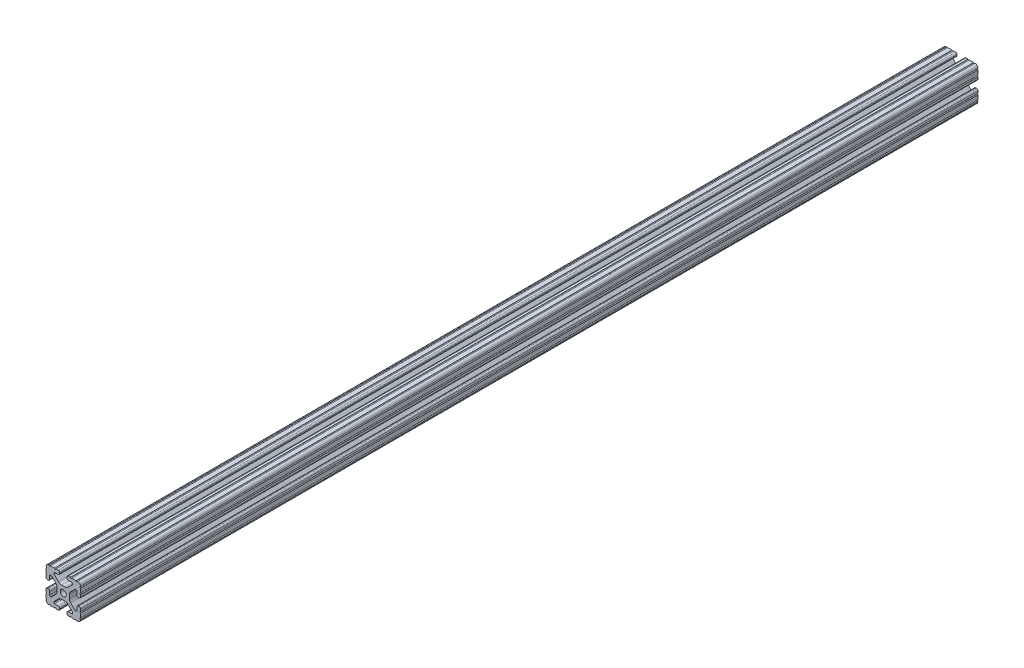
SolidWorks part; units mm, degrees
material "6061 Alloy"
ref_plane "Front Plane" through (0, 0, 0) normal (0, 0, 1) x (1, 0, 0)
ref_plane "Top Plane" through (0, 0, 0) normal (0, 1, 0) x (1, 0, 0)
ref_plane "Right Plane" through (0, 0, 0) normal (1, 0, 0) x (0, 0, -1)
sketch "Sketch1" plane through (0, 0, 0) normal (0, 0, 1) x (1, 0, 0)
  line L0 (0, 25.6181) -> (0, -24.623) construction
  line L1 (-20.8943, 0) -> (20.4607, 0) construction
  line L2 (-10.0229, 12.9148) -> (-5.2522, 8.144)
  line L3 (-10.287, 14.0843) -> (-10.287, 13.5524)
  line L4 (-5.6176, 14.986) -> (-9.3853, 14.986)
  line L5 (-4.064, 17.4964) -> (-4.064, 16.5396)
  line L6 (-7.9742, 19.05) -> (-5.6176, 19.05)
  line L7 (-14.3277, 19.05) -> (-9.4982, 19.05)
  line L8 (-19.05, 9.4961) -> (-19.05, 14.3277)
  line L9 (-19.05, 5.6176) -> (-19.05, 7.9763)
  line L10 (-16.5396, 4.064) -> (-17.4964, 4.064)
  line L11 (-14.986, 9.3853) -> (-14.986, 5.6176)
  line L12 (-13.516, 10.287) -> (-14.0843, 10.287)
  line L13 (-8.1476, 5.2921) -> (-12.8784, 10.0229)
  line L14 (-6.7564, -1.9335) -> (-6.7564, 1.9335)
  line L15 (-12.8784, -10.0229) -> (-8.1476, -5.2921)
  line L16 (-14.0843, -10.287) -> (-13.516, -10.287)
  line L17 (-14.986, -5.6176) -> (-14.986, -9.3853)
  line L18 (-17.4964, -4.064) -> (-16.5396, -4.064)
  line L19 (-19.05, -7.9763) -> (-19.05, -5.6176)
  line L20 (-19.05, -14.3277) -> (-19.05, -9.4961)
  line L21 (-9.4961, -19.05) -> (-14.3277, -19.05)
  line L22 (-5.6176, -19.05) -> (-7.9763, -19.05)
  line L23 (-4.064, -17.4964) -> (-4.064, -16.5396)
  line L24 (10.0229, -12.9148) -> (5.2522, -8.144)
  line L25 (10.287, -14.0843) -> (10.287, -13.5524)
  line L26 (5.6176, -14.986) -> (9.3853, -14.986)
  line L28 (-1.9022, 6.7564) -> (1.9022, 6.7564)
  line L29 (-1.9022, -6.7564) -> (1.9022, -6.7564)
  line L31 (-5.6176, -14.986) -> (-9.3853, -14.986)
  line L32 (-10.287, -14.0843) -> (-10.287, -13.5524)
  line L33 (-10.0229, -12.9148) -> (-5.2522, -8.144)
  line L66 (4.064, -16.5396) -> (4.064, -17.4964)
  line L67 (5.6176, -19.05) -> (7.9763, -19.05)
  line L68 (9.4961, -19.05) -> (14.3277, -19.05)
  line L69 (19.05, -14.3277) -> (19.05, -9.4961)
  line L70 (19.05, -7.9763) -> (19.05, -5.6176)
  line L71 (17.4964, -4.064) -> (16.5396, -4.064)
  line L72 (14.986, -5.6176) -> (14.986, -9.3853)
  line L73 (14.0843, -10.287) -> (13.516, -10.287)
  line L74 (12.8784, -10.0229) -> (8.1476, -5.2921)
  line L75 (6.7564, -1.9335) -> (6.7564, 1.9335)
  line L76 (8.1476, 5.2921) -> (12.8784, 10.0229)
  line L77 (13.516, 10.287) -> (14.0843, 10.287)
  line L78 (14.986, 9.3853) -> (14.986, 5.6176)
  line L79 (16.5396, 4.064) -> (17.4964, 4.064)
  line L80 (19.05, 5.6176) -> (19.05, 7.9763)
  line L81 (19.05, 9.4961) -> (19.05, 14.3277)
  line L82 (14.3277, 19.05) -> (9.4982, 19.05)
  line L83 (7.9742, 19.05) -> (5.6176, 19.05)
  line L84 (4.064, 17.4964) -> (4.064, 16.5396)
  line L85 (5.6176, 14.986) -> (9.3853, 14.986)
  line L86 (10.287, 14.0843) -> (10.287, 13.5524)
  line L87 (10.0229, 12.9148) -> (5.2522, 8.144)
  arc A0 (-10.0229, 12.9148) -> (-10.287, 13.5524) centre (-9.3853, 13.5524) cw
  circle A1 centre (0, 0) radius 3.3274
  arc A2 (-10.287, 14.0843) -> (-9.3853, 14.986) centre (-9.3853, 14.0843) cw
  arc A3 (-4.064, 16.5396) -> (-5.6176, 14.986) centre (-5.6176, 16.5396) cw
  arc A4 (-5.6176, 19.05) -> (-4.064, 17.4964) centre (-5.6176, 17.4964) cw
  arc A5 (-7.9742, 19.05) -> (-9.4982, 19.05) centre (-8.7362, 19.05) cw
  arc A6 (-14.3277, 19.05) -> (-15.8475, 19.05) centre (-15.0876, 18.9933) cw
  arc A7 (-19.05, 15.8475) -> (-15.8475, 19.05) centre (-15.8751, 15.8751) cw
  arc A8 (-19.05, 15.8475) -> (-19.05, 14.3277) centre (-18.9933, 15.0876) cw
  arc A9 (-19.05, 9.4961) -> (-19.05, 7.9763) centre (-18.9933, 8.7362) cw
  arc A10 (-17.4964, 4.064) -> (-19.05, 5.6176) centre (-17.4964, 5.6176) cw
  arc A11 (-14.986, 5.6176) -> (-16.5396, 4.064) centre (-16.5396, 5.6176) cw
  arc A12 (-14.986, 9.3853) -> (-14.0843, 10.287) centre (-14.0843, 9.3853) cw
  arc A13 (-13.516, 10.287) -> (-12.8784, 10.0229) centre (-13.516, 9.3853) cw
  arc A14 (-8.1476, 5.2921) -> (-6.7564, 1.9335) centre (-11.5062, 1.9335) cw
  arc A15 (-6.7564, -1.9335) -> (-8.1476, -5.2921) centre (-11.5062, -1.9335) cw
  arc A16 (-12.8784, -10.0229) -> (-13.516, -10.287) centre (-13.516, -9.3853) cw
  arc A17 (-14.0843, -10.287) -> (-14.986, -9.3853) centre (-14.0843, -9.3853) cw
  arc A18 (-16.5396, -4.064) -> (-14.986, -5.6176) centre (-16.5396, -5.6176) cw
  arc A19 (-19.05, -5.6176) -> (-17.4964, -4.064) centre (-17.4964, -5.6176) cw
  arc A20 (-19.05, -7.9763) -> (-19.05, -9.4961) centre (-18.9933, -8.7362) cw
  arc A21 (-19.05, -14.3277) -> (-19.05, -15.8475) centre (-18.9933, -15.0876) cw
  arc A22 (-15.8475, -19.05) -> (-19.05, -15.8475) centre (-15.8751, -15.8751) cw
  arc A23 (-15.8475, -19.05) -> (-14.3277, -19.05) centre (-15.0876, -18.9933) cw
  arc A24 (-9.4961, -19.05) -> (-7.9763, -19.05) centre (-8.7362, -18.9933) cw
  arc A25 (-4.064, -17.4964) -> (-5.6176, -19.05) centre (-5.6176, -17.4964) cw
  arc A26 (-5.2522, -8.144) -> (-1.9022, -6.7564) centre (-1.9022, -11.494) cw
  arc A27 (1.9022, -6.7564) -> (5.2522, -8.144) centre (1.9022, -11.494) cw
  arc A28 (10.0229, -12.9148) -> (10.287, -13.5524) centre (9.3853, -13.5524) cw
  arc A29 (10.287, -14.0843) -> (9.3853, -14.986) centre (9.3853, -14.0843) cw
  arc A30 (4.064, -16.5396) -> (5.6176, -14.986) centre (5.6176, -16.5396) cw
  arc A31 (-4.064, -16.5396) -> (-5.6176, -14.986) centre (-5.6176, -16.5396) ccw
  arc A32 (-10.287, -14.0843) -> (-9.3853, -14.986) centre (-9.3853, -14.0843) ccw
  arc A33 (-10.0229, -12.9148) -> (-10.287, -13.5524) centre (-9.3853, -13.5524) ccw
  arc A79 (4.064, -17.4964) -> (5.6176, -19.05) centre (5.6176, -17.4964) ccw
  arc A80 (9.4961, -19.05) -> (7.9763, -19.05) centre (8.7362, -18.9933) ccw
  arc A81 (15.8475, -19.05) -> (14.3277, -19.05) centre (15.0876, -18.9933) ccw
  arc A82 (15.8475, -19.05) -> (19.05, -15.8475) centre (15.8751, -15.8751) ccw
  arc A83 (19.05, -14.3277) -> (19.05, -15.8475) centre (18.9933, -15.0876) ccw
  arc A84 (19.05, -7.9763) -> (19.05, -9.4961) centre (18.9933, -8.7362) ccw
  arc A85 (19.05, -5.6176) -> (17.4964, -4.064) centre (17.4964, -5.6176) ccw
  arc A86 (16.5396, -4.064) -> (14.986, -5.6176) centre (16.5396, -5.6176) ccw
  arc A87 (14.0843, -10.287) -> (14.986, -9.3853) centre (14.0843, -9.3853) ccw
  arc A88 (12.8784, -10.0229) -> (13.516, -10.287) centre (13.516, -9.3853) ccw
  arc A89 (6.7564, -1.9335) -> (8.1476, -5.2921) centre (11.5062, -1.9335) ccw
  arc A90 (8.1476, 5.2921) -> (6.7564, 1.9335) centre (11.5062, 1.9335) ccw
  arc A91 (13.516, 10.287) -> (12.8784, 10.0229) centre (13.516, 9.3853) ccw
  arc A92 (14.986, 9.3853) -> (14.0843, 10.287) centre (14.0843, 9.3853) ccw
  arc A93 (14.986, 5.6176) -> (16.5396, 4.064) centre (16.5396, 5.6176) ccw
  arc A94 (17.4964, 4.064) -> (19.05, 5.6176) centre (17.4964, 5.6176) ccw
  arc A95 (19.05, 9.4961) -> (19.05, 7.9763) centre (18.9933, 8.7362) ccw
  arc A96 (19.05, 15.8475) -> (19.05, 14.3277) centre (18.9933, 15.0876) ccw
  arc A97 (19.05, 15.8475) -> (15.8475, 19.05) centre (15.8751, 15.8751) ccw
  arc A98 (14.3277, 19.05) -> (15.8475, 19.05) centre (15.0876, 18.9933) ccw
  arc A99 (7.9742, 19.05) -> (9.4982, 19.05) centre (8.7362, 19.05) ccw
  arc A100 (5.6176, 19.05) -> (4.064, 17.4964) centre (5.6176, 17.4964) ccw
  arc A101 (4.064, 16.5396) -> (5.6176, 14.986) centre (5.6176, 16.5396) ccw
  arc A102 (10.287, 14.0843) -> (9.3853, 14.986) centre (9.3853, 14.0843) ccw
  arc A103 (10.0229, 12.9148) -> (10.287, 13.5524) centre (9.3853, 13.5524) ccw
  arc A104 (1.9022, 6.7564) -> (5.2522, 8.144) centre (1.9022, 11.494) ccw
  arc A105 (-5.2522, 8.144) -> (-1.9022, 6.7564) centre (-1.9022, 11.494) ccw
  dimension "D1" = 6.6548
  dimension "D2" = 19.05
  dimension "D3" = 38.1
  dimension "D4" = 20.574
  dimension "D5" = 13.5128
  dimension "D6" = 4.064
  dimension "D7" = 8.128
  dimension "D8" = 4.064
  dimension "D9" = 12.2936
extrude "Extrude1" add sketch "Sketch1" against normal blind 990.6
